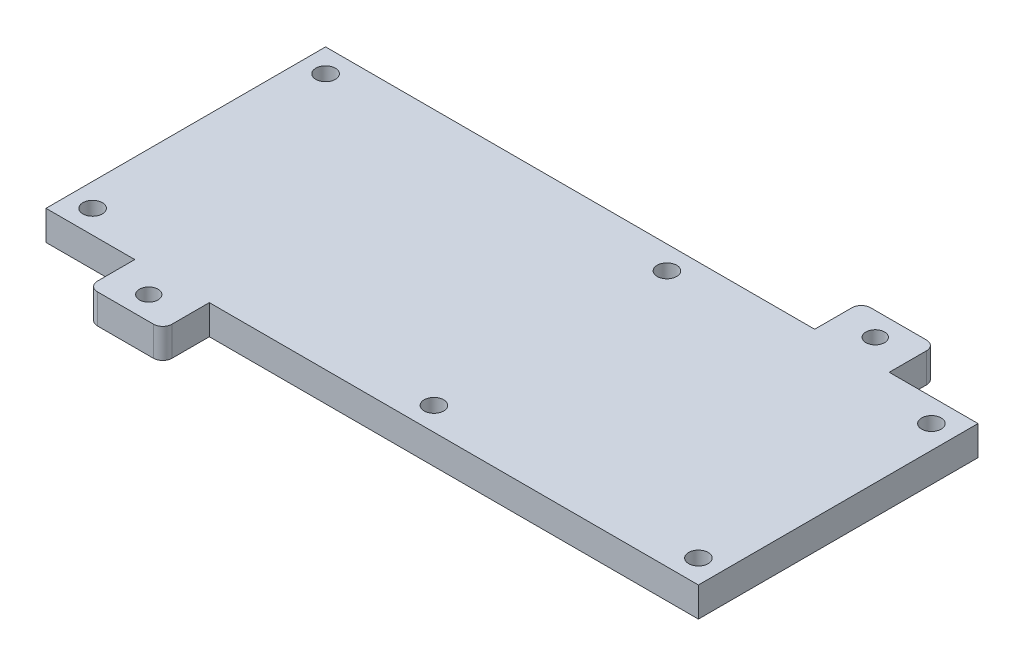
SolidWorks part; units mm, degrees
material "Custom Plastic"
ref_plane "X-Y Datum" through (0, 0, 0) normal (0, 0, 1) x (1, 0, 0)
ref_plane "X-Z Datum" through (0, 0, 0) normal (0, 1, 0) x (1, 0, 0)
ref_plane "Y-Z Datum" through (0, 0, 0) normal (1, 0, 0) x (0, 0, -1)
sketch "Sketch1" plane through (0, 0, 0) normal (0, -1, 0) x (1, 0, 0)
  line L1 (-78.25, 30) -> (61.75, 30)
  line L2 (-78.25, 30) -> (-78.25, -30)
  line L3 (-78.25, -30) -> (61.75, -30)
  line L4 (61.75, 30) -> (61.75, -30)
  circle A0 centre (-73.25, 25) radius 2.0955
  circle A1 centre (0, 25) radius 2.0955
  circle A2 centre (56.75, 25) radius 2.0955
  circle A3 centre (56.75, -25) radius 2.0955
  circle A4 centre (0, -25) radius 2.0955
  circle A5 centre (-73.25, -25) radius 2.0955
extrude "Boss-Extrude1" add sketch "Sketch1" along normal blind 6.35
sketch "Sketch2" plane through (0, -6.35, 0) normal (0, -1, 0) x (1, 0, 0)
  line L0 (-78.25, -30) -> (61.75, -30) construction
  line L1 (42.7, -30) -> (26.7, -30)
  line L2 (42.7, -30) -> (42.7, -40)
  line L3 (42.7, -40) -> (26.7, -40)
  line L4 (26.7, -30) -> (26.7, -40)
  line L5 (61.75, -30) -> (61.75, 30) construction
  line L6 (34.7, -40) -> (34.7, -30) construction
  line L18 (-51.2, 40) -> (-51.2, 30) construction
  line L19 (-59.2, 30) -> (-59.2, 40)
  line L20 (-43.2, 30) -> (-43.2, 40)
  line L21 (-59.2, 30) -> (-43.2, 30)
  line L22 (-59.2, 30) -> (-59.2, 40)
  line L23 (-59.2, 40) -> (-43.2, 40)
  line L24 (-43.2, 30) -> (-43.2, 40)
  circle A0 centre (34.7, -35) radius 2
  circle A2 centre (-51.2, 35) radius 2
  line M12 (-78.25, -30) -> (61.75, -30)
  line M14 (61.75, 30) -> (-78.25, 30)
  dimension "D4" = 4
  dimension "D1" = 19.05
  dimension "D2" = 16
  dimension "D3" = 10
extrude "Boss-Extrude2" add sketch "Sketch2" against normal blind 6.35 contours L4 L3 L2 A0 M12 | L23 L19 L20 A2 M14
fillet "Fillet1" radius 2 4 edges at (-43.2, -3.175, 40) (-59.2, -3.175, 40) (26.7, -3.175, -40) (42.7, -3.175, -40)
